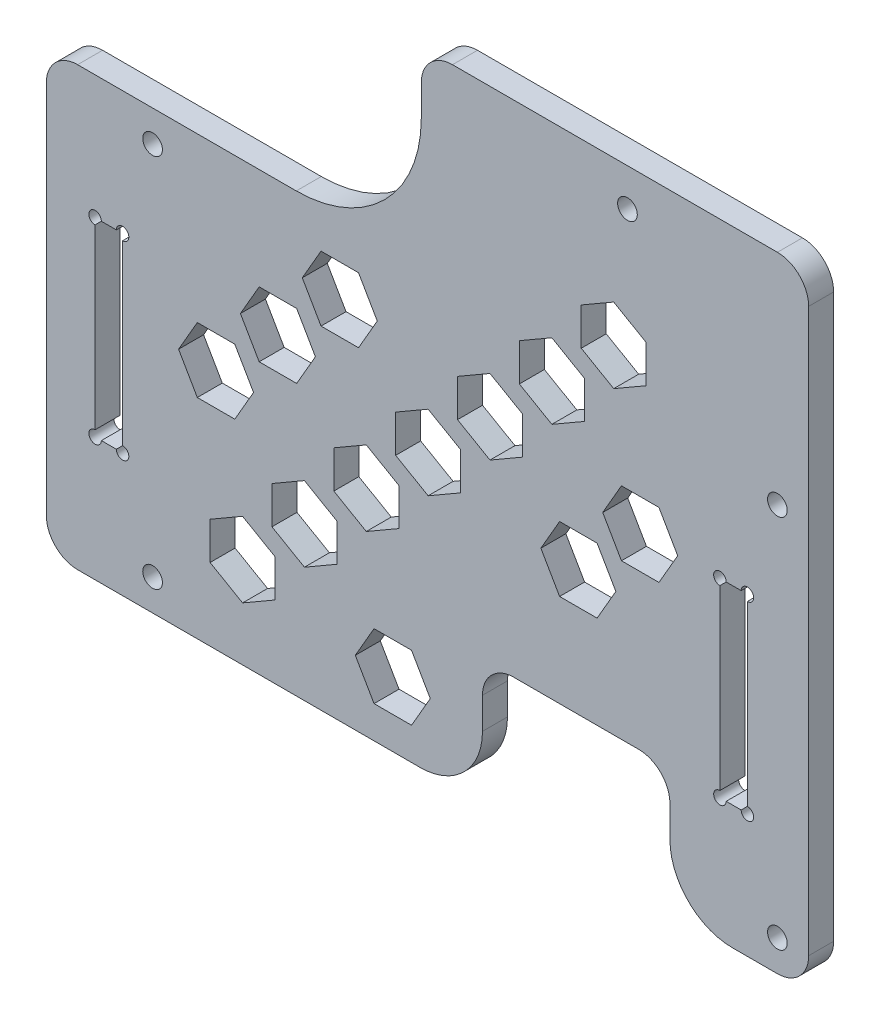
SolidWorks part; units mm, degrees
ref_plane "前视基准面" through (0, 0, 0) normal (0, 0, 1) x (1, 0, 0)
ref_plane "上视基准面" through (0, 0, 0) normal (0, 1, 0) x (1, 0, 0)
ref_plane "右视基准面" through (0, 0, 0) normal (1, 0, 0) x (0, 0, -1)
other "Configuration Table"
sketch "草图1" plane through (0, 0, 0) normal (0, 0, 1) x (1, 0, 0)
  line L1 (0, 0) -> (120, 0)
  line L2 (0, 0) -> (0, -70)
  line L3 (0, -70) -> (120, -70)
  line L4 (120, 0) -> (120, -70)
  dimension "D1" = 120
  dimension "D2" = 70
extrude "凸台-拉伸1" add sketch "草图1" along normal blind 4 contours L1 L4 L3 L2
sketch "草图2" plane through (0, 0, 4) normal (0, 0, 1) x (1, 0, 0)
  line L0 (110, -19.8) -> (110, -50.2) construction
  line L1 (7.8, -19.8) -> (12.2, -19.8)
  line L2 (7.8, -19.8) -> (7.8, -50.2)
  line L3 (7.8, -50.2) -> (12.2, -50.2)
  line L4 (12.2, -19.8) -> (12.2, -50.2)
  line L5 (120, -35) -> (0, -35) construction
  line L6 (120, 0) -> (120, -70) construction
  line L7 (0, 0) -> (0, -70) construction
  line L8 (60, 0) -> (60, -70) construction
  line L9 (0, 0) -> (120, 0) construction
  line L10 (0, -70) -> (120, -70) construction
  line L11 (10, -19.8) -> (10, -50.2) construction
  line L13 (107.8, -19.8) -> (107.8, -50.2)
  line L14 (112.2, -50.2) -> (107.8, -50.2)
  line L15 (112.2, -19.8) -> (112.2, -50.2)
  line L16 (112.2, -19.8) -> (107.8, -19.8)
  dimension "D1" = 4.4
  dimension "D2" = 30.4
  dimension "D3" = 100
extrude "切除-拉伸1" cut sketch "草图2" against normal through all
sketch "草图3" plane through (0, 0, 4) normal (0, 0, 1) x (1, 0, 0)
  line L1 (0, 0) -> (120, 0) construction
  line L2 (120, -35) -> (0, -35) construction
  line L3 (120, 0) -> (120, -70) construction
  line L4 (0, 0) -> (0, -70) construction
  line L6 (10, -19.8) -> (10, -50.2) construction
  line L7 (12.2, -19.8) -> (7.8, -19.8) construction
  line L8 (7.8, -50.2) -> (12.2, -50.2) construction
  line L9 (110, -19.8) -> (110, -50.2) construction
  line L10 (112.2, -19.8) -> (107.8, -19.8) construction
  line L11 (107.8, -50.2) -> (112.2, -50.2) construction
  circle A0 centre (7.8, -19.8) radius 1
  circle A1 centre (12.2, -19.8) radius 1
  circle A2 centre (7.8, -50.2) radius 1
  circle A3 centre (12.2, -50.2) radius 1
  circle A4 centre (107.8, -19.8) radius 1
  circle A5 centre (107.8, -50.2) radius 1
  circle A6 centre (112.2, -50.2) radius 1
  circle A7 centre (112.2, -19.8) radius 1
  circle A8 centre (17, -5) radius 1.575
  circle A9 centre (17, -65) radius 1.575
  circle A10 centre (117, -5) radius 1.575
  circle A11 centre (117, -65) radius 1.575
  dimension "D1" = 3.15
  dimension "D2" = 2
  dimension "D3" = 7
  dimension "D5" = 3.15
  dimension "D4" = 5
  dimension "D6" = 7
  dimension "D7" = 5
extrude "切除-拉伸2" cut sketch "草图3" against normal through all
sketch "草图4" plane through (0, 0, 4) normal (0, 0, 1) x (1, 0, 0)
  line L0 (60, 0) -> (60, 30)
  line L1 (0, 0) -> (120, 0) construction
  line L4 (120, 0) -> (60, 0)
  line L5 (60, 30) -> (122, 30)
  line L6 (122, 30) -> (122, -70)
  line L7 (122, -70) -> (120, -70)
  line L8 (0, -70) -> (120, -70) construction
  line L9 (120, 0) -> (120, -70)
  dimension "D1" = 2
  dimension "D2" = 30
extrude "凸台-拉伸2" add sketch "草图4" against normal blind 4
sketch "草图5" plane through (0, 0, 4) normal (0, 0, 1) x (1, 0, 0)
  line L0 (107.8, -20.8) -> (107.8, -49.2) construction
  line L1 (122, 30) -> (60, 30) construction
  line L2 (0, -70) -> (122, -70) construction
  line L3 (69.8, -70) -> (99.8, -70)
  line L4 (69.8, -70) -> (69.8, -50)
  line L5 (69.8, -50) -> (99.8, -50)
  line L6 (99.8, -70) -> (99.8, -50)
  line L7 (110, -19.8) -> (110, -50.2) construction
  line L8 (111.2, -19.8) -> (108.8, -19.8) construction
  line L9 (108.8, -50.2) -> (111.2, -50.2) construction
  line L13 (90.8, 4) -> (16.8, -70) construction
  line L14 (90.8, -2) -> (95.9962, 1)
  line L15 (95.9962, 1) -> (95.9962, 7)
  line L16 (95.9962, 7) -> (90.8, 10)
  line L17 (90.8, 10) -> (85.6038, 7)
  line L18 (85.6038, 7) -> (85.6038, 1)
  line L19 (85.6038, 1) -> (90.8, -2)
  line L20 (0, -70) -> (122, -70) construction
  line L21 (86.0967, -2.8995) -> (80.9005, 0.1005)
  line L22 (86.0967, -8.8995) -> (86.0967, -2.8995)
  line L23 (80.9005, -11.8995) -> (86.0967, -8.8995)
  line L24 (75.7044, -8.8995) -> (80.9005, -11.8995)
  line L25 (75.7044, -2.8995) -> (75.7044, -8.8995)
  line L26 (80.9005, 0.1005) -> (75.7044, -2.8995)
  line L27 (76.1972, -12.799) -> (71.001, -9.799)
  line L28 (76.1972, -18.799) -> (76.1972, -12.799)
  line L29 (71.001, -21.799) -> (76.1972, -18.799)
  line L30 (65.8049, -18.799) -> (71.001, -21.799)
  line L31 (65.8049, -12.799) -> (65.8049, -18.799)
  line L32 (71.001, -9.799) -> (65.8049, -12.799)
  line L33 (66.2977, -22.6985) -> (61.1015, -19.6985)
  line L34 (66.2977, -28.6985) -> (66.2977, -22.6985)
  line L35 (61.1015, -31.6985) -> (66.2977, -28.6985)
  line L36 (55.9054, -28.6985) -> (61.1015, -31.6985)
  line L37 (55.9054, -22.6985) -> (55.9054, -28.6985)
  line L38 (61.1015, -19.6985) -> (55.9054, -22.6985)
  line L39 (56.3982, -32.598) -> (51.202, -29.598)
  line L40 (56.3982, -38.598) -> (56.3982, -32.598)
  line L41 (51.202, -41.598) -> (56.3982, -38.598)
  line L42 (46.0059, -38.598) -> (51.202, -41.598)
  line L43 (46.0059, -32.598) -> (46.0059, -38.598)
  line L44 (51.202, -29.598) -> (46.0059, -32.598)
  line L45 (46.4987, -42.4975) -> (41.3025, -39.4975)
  line L46 (46.4987, -48.4975) -> (46.4987, -42.4975)
  line L47 (41.3025, -51.4975) -> (46.4987, -48.4975)
  line L48 (36.1064, -48.4975) -> (41.3025, -51.4975)
  line L49 (36.1064, -42.4975) -> (36.1064, -48.4975)
  line L50 (41.3025, -39.4975) -> (36.1064, -42.4975)
  line L51 (36.5992, -52.397) -> (31.403, -49.397)
  line L52 (36.5992, -58.397) -> (36.5992, -52.397)
  line L53 (31.403, -61.397) -> (36.5992, -58.397)
  line L54 (26.2069, -58.397) -> (31.403, -61.397)
  line L55 (26.2069, -52.397) -> (26.2069, -58.397)
  line L56 (31.403, -49.397) -> (26.2069, -52.397)
  line L57 (122, 21.0579) -> (16.8, -84.1421) construction
  line L58 (122, -70) -> (122, 30) construction
  line L59 (107.8579, 35.2) -> (2.6579, -70) construction
  line L60 (91.1431, -29.9411) -> (88.1431, -35.1373)
  line L61 (88.1431, -35.1373) -> (82.1431, -35.1373)
  line L62 (82.1431, -35.1373) -> (79.1431, -29.9411)
  line L63 (79.1431, -29.9411) -> (82.1431, -24.745)
  line L64 (82.1431, -24.745) -> (88.1431, -24.745)
  line L65 (88.1431, -24.745) -> (91.1431, -29.9411)
  line L66 (101.0426, -20.0416) -> (98.0426, -25.2378)
  line L67 (98.0426, -25.2378) -> (92.0426, -25.2378)
  line L68 (92.0426, -25.2378) -> (89.0426, -20.0416)
  line L69 (89.0426, -20.0416) -> (92.0426, -14.8455)
  line L70 (92.0426, -14.8455) -> (98.0426, -14.8455)
  line L71 (98.0426, -14.8455) -> (101.0426, -20.0416)
  line L72 (61.4447, -59.6396) -> (58.4447, -64.8358)
  line L73 (58.4447, -64.8358) -> (52.4447, -64.8358)
  line L74 (52.4447, -64.8358) -> (49.4447, -59.6396)
  line L75 (49.4447, -59.6396) -> (52.4447, -54.4435)
  line L76 (52.4447, -54.4435) -> (58.4447, -54.4435)
  line L77 (58.4447, -54.4435) -> (61.4447, -59.6396)
  line L78 (31.0599, -21.4558) -> (34.0599, -16.2597)
  line L79 (30.1604, -36.5515) -> (24.1604, -36.5515)
  line L80 (24.1604, -36.5515) -> (21.1604, -31.3553)
  line L81 (21.1604, -31.3553) -> (24.1604, -26.1592)
  line L82 (24.1604, -26.1592) -> (30.1604, -26.1592)
  line L83 (30.1604, -26.1592) -> (33.1604, -31.3553)
  line L84 (33.1604, -31.3553) -> (30.1604, -36.5515)
  line L85 (40.0599, -26.652) -> (34.0599, -26.652)
  line L86 (34.0599, -26.652) -> (31.0599, -21.4558)
  line L87 (34.0599, -16.2597) -> (40.0599, -16.2597)
  line L88 (40.0599, -16.2597) -> (43.0599, -21.4558)
  line L89 (43.0599, -21.4558) -> (40.0599, -26.652)
  line L90 (43.9594, -16.7525) -> (40.9594, -11.5563)
  line L91 (40.9594, -11.5563) -> (43.9594, -6.3602)
  line L92 (43.9594, -6.3602) -> (49.9594, -6.3602)
  line L93 (49.9594, -6.3602) -> (52.9594, -11.5563)
  line L94 (49.9594, -16.7525) -> (43.9594, -16.7525)
  line L95 (52.9594, -11.5563) -> (49.9594, -16.7525)
  circle A0 centre (93, 24) radius 1.575
  circle A1 centre (90.8, 4) radius 5.1962 construction
  point P67 (122, 21.0594)
  point P70 (31.403, -70)
  point P109 (2.505, -70)
  point P110 (16.8, -84.1421)
  point P111 (16.8, -84.1421)
  dimension "D1" = 3.15
  dimension "D2" = 17
  dimension "D3" = 6
  dimension "D4" = 8
  dimension "D5" = 30
  dimension "D6" = 20
  dimension "D7" = 6
  dimension "D8" = 17
  dimension "D9" = 20
  dimension "D10" = 45
  dimension "D12" = 13.523
  dimension "D13" = 10
  dimension "D11" = 7
extrude "切除-拉伸3" cut sketch "草图5" against normal through all
fillet "圆角1" radius 10 2 edges at (69.8, -70, 2) (99.8, -70, 2)
fillet "圆角2" radius 5 7 edges at (99.8, -50, 2) (69.8, -50, 2) (60, 30, 2) (0, 0, 2) (0, -70, 2) (122, -70, 2) (122, 30, 2)
fillet "圆角3" radius 20 1 edges at (60, 0, 2)
